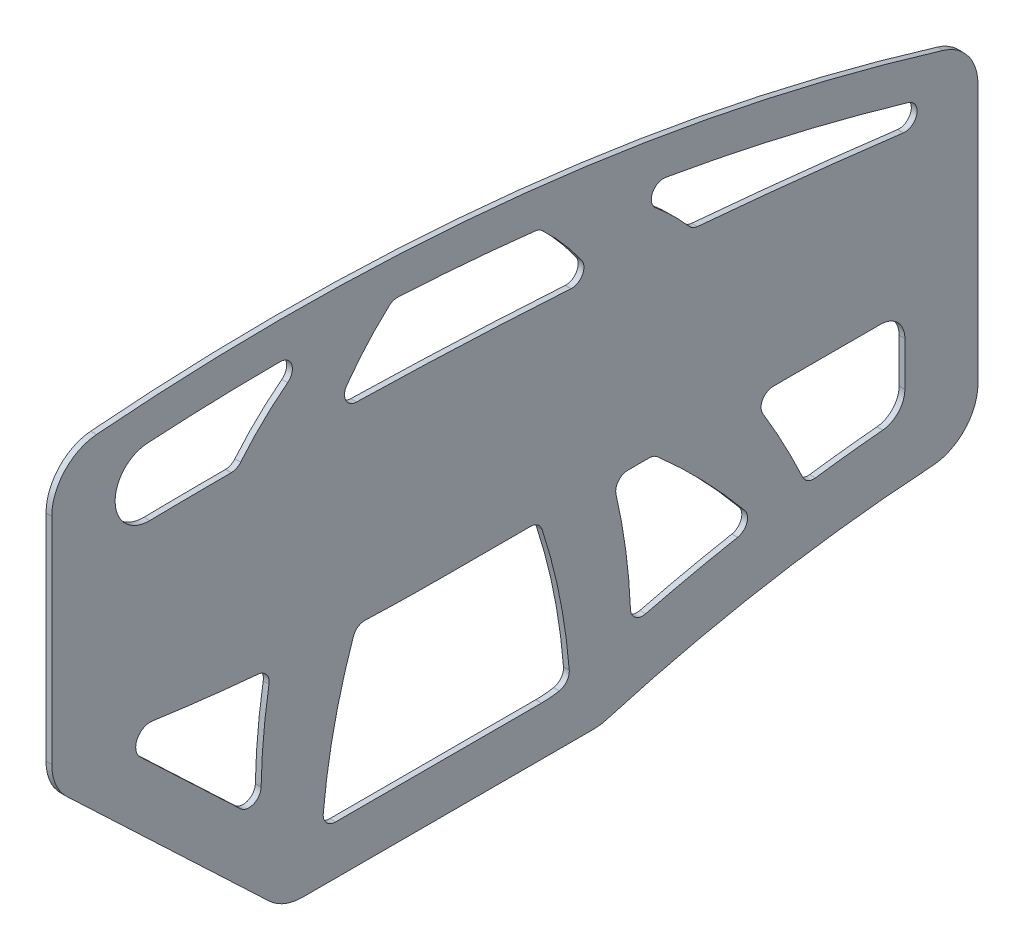
SolidWorks part; units mm, degrees
ref_plane "Front Plane" through (0, 0, 0) normal (0, 0, 1) x (1, 0, 0)
ref_plane "Top Plane" through (0, 0, 0) normal (0, 1, 0) x (1, 0, 0)
ref_plane "Right Plane" through (0, 0, 0) normal (1, 0, 0) x (0, 0, -1)
sketch "Sketch3" plane through (0, 0, 0) normal (1, 0, 0) x (0, 0, -1)
  line L0 (296.2756, -106.7625) -> (296.2756, 28.1835) construction
  line L1 (-55.5532, -162.7221) -> (95.7836, -162.7221) construction
  line L2 (-178.3931, -55.9359) -> (-73.0219, -155.7613) construction
  line L3 (-186.3244, 74.4801) -> (-186.3244, -37.4967) construction
  line L4 (296.2756, -106.7625) -> (296.2756, 28.1835)
  line L5 (-55.5532, -162.7221) -> (95.7836, -162.7221)
  line L6 (-178.3931, -55.9359) -> (-73.0219, -155.7613)
  line L7 (-186.3244, 74.4801) -> (-186.3244, -37.4967)
  line L8 (-140.2016, -57.1289) -> (-87.9677, -106.6136) construction
  line L9 (-140.2016, -57.1289) -> (-87.9677, -106.6136)
  line L10 (63.1095, -54.7721) -> (16.8756, -54.7721) construction
  line L11 (-38.5414, -137.3221) -> (68.868, -137.3221) construction
  line L12 (63.1095, -54.7721) -> (16.8756, -54.7721)
  line L13 (-38.5414, -137.3221) -> (68.868, -137.3221)
  line L14 (124.985, -54.7721) -> (113.8651, -54.7721) construction
  line L15 (124.985, -54.7721) -> (113.8651, -54.7721)
  line L16 (258.1756, -90.4176) -> (258.1756, -67.4721) construction
  line L17 (245.4756, -54.7721) -> (189.6005, -54.7721) construction
  line L18 (245.4756, -54.7721) -> (189.6005, -54.7721)
  line L19 (258.1756, -90.4176) -> (258.1756, -67.4721)
  arc A0 (296.2756, 28.1835) -> (278.2931, 52.4763) centre (270.8756, 28.1835) ccw construction
  arc A1 (272.4753, -132.1121) -> (296.2756, -106.7625) centre (270.8756, -106.7625) ccw construction
  arc A2 (95.7836, -162.7221) -> (102.8656, -161.7148) centre (95.7836, -137.3221) ccw construction
  arc A3 (272.4753, -132.1121) -> (102.8656, -161.7148) centre (321.9663, -916.3645) ccw construction
  arc A4 (-73.0219, -155.7613) -> (-55.5532, -162.7221) centre (-55.5532, -137.3221) ccw construction
  arc A5 (-186.3244, -37.4967) -> (-178.3931, -55.9359) centre (-160.9244, -37.4967) ccw construction
  arc A6 (-163.0233, 99.7932) -> (-186.3244, 74.4801) centre (-160.9244, 74.4801) ccw construction
  arc A7 (278.2931, 52.4763) -> (-163.0233, 99.7932) centre (-65.6891, -1074.0863) ccw construction
  arc A8 (296.2756, 28.1835) -> (278.2931, 52.4763) centre (270.8756, 28.1835) ccw
  arc A9 (272.4753, -132.1121) -> (296.2756, -106.7625) centre (270.8756, -106.7625) ccw
  arc A10 (95.7836, -162.7221) -> (102.8656, -161.7148) centre (95.7836, -137.3221) ccw
  arc A11 (272.4753, -132.1121) -> (102.8656, -161.7148) centre (321.9663, -916.3645) ccw
  arc A12 (-73.0219, -155.7613) -> (-55.5532, -162.7221) centre (-55.5532, -137.3221) ccw
  arc A13 (-186.3244, -37.4967) -> (-178.3931, -55.9359) centre (-160.9244, -37.4967) ccw
  arc A14 (-163.0233, 99.7932) -> (-186.3244, 74.4801) centre (-160.9244, 74.4801) ccw
  arc A15 (278.2931, 52.4763) -> (-163.0233, 99.7932) centre (-65.6891, -1074.0863) ccw
  arc A16 (-63.4237, 73.3867) -> (-67.3033, 84.7705) centre (-67.2945, 78.4205) ccw construction
  arc A17 (-67.3033, 84.7705) -> (-136.6126, 82.5993) centre (-65.6891, -1074.0863) ccw construction
  arc A18 (-136.6126, 82.5993) -> (-135.2401, 47.0749) centre (-135.5244, 64.8526) ccw construction
  arc A19 (-92.8258, 47.4311) -> (-135.2401, 47.0749) centre (-90.5684, -2746.568) ccw construction
  arc A20 (-92.8258, 47.4311) -> (-87.9387, 49.7329) centre (-92.831, 53.7811) ccw construction
  arc A21 (-63.4237, 73.3867) -> (-87.9387, 49.7329) centre (29.4753, -47.4253) ccw construction
  arc A22 (-63.4237, 73.3867) -> (-67.3033, 84.7705) centre (-67.2945, 78.4205) ccw
  arc A23 (-67.3033, 84.7705) -> (-136.6126, 82.5993) centre (-65.6891, -1074.0863) ccw
  arc A24 (-136.6126, 82.5993) -> (-135.2401, 47.0749) centre (-135.5244, 64.8526) ccw
  arc A25 (-92.8258, 47.4311) -> (-135.2401, 47.0749) centre (-90.5684, -2746.568) ccw
  arc A26 (-92.8258, 47.4311) -> (-87.9387, 49.7329) centre (-92.831, 53.7811) ccw
  arc A27 (-63.4237, 73.3867) -> (-87.9387, 49.7329) centre (29.4753, -47.4253) ccw
  arc A28 (69.2315, 75.6347) -> (65.6099, 77.3095) centre (64.8904, 71.0004) ccw construction
  arc A29 (89.7981, 51.9454) -> (69.2315, 75.6347) centre (-34.9549, -35.5901) ccw construction
  arc A30 (84.2029, 41.9605) -> (89.7981, 51.9454) centre (84.6001, 48.2981) ccw construction
  arc A31 (84.2029, 41.9605) -> (-27.5702, 46.7217) centre (-90.5684, -2746.568) ccw construction
  arc A32 (-32.6046, 56.7463) -> (-27.5702, 46.7217) centre (-27.427, 53.0701) ccw construction
  arc A33 (-10.5082, 81.5997) -> (-32.6046, 56.7463) centre (91.6585, -31.4832) ccw construction
  arc A34 (-5.9237, 83.2295) -> (-10.5082, 81.5997) centre (-6.2512, 76.8879) ccw construction
  arc A35 (65.6099, 77.3095) -> (-5.9237, 83.2295) centre (-65.6891, -1074.0863) ccw construction
  arc A36 (69.2315, 75.6347) -> (65.6099, 77.3095) centre (64.8904, 71.0004) ccw
  arc A37 (89.7981, 51.9454) -> (69.2315, 75.6347) centre (-34.9549, -35.5901) ccw
  arc A38 (84.2029, 41.9605) -> (89.7981, 51.9454) centre (84.6001, 48.2981) ccw
  arc A39 (84.2029, 41.9605) -> (-27.5702, 46.7217) centre (-90.5684, -2746.568) ccw
  arc A40 (-32.6046, 56.7463) -> (-27.5702, 46.7217) centre (-27.427, 53.0701) ccw
  arc A41 (-10.5082, 81.5997) -> (-32.6046, 56.7463) centre (91.6585, -31.4832) ccw
  arc A42 (-5.9237, 83.2295) -> (-10.5082, 81.5997) centre (-6.2512, 76.8879) ccw
  arc A43 (65.6099, 77.3095) -> (-5.9237, 83.2295) centre (-65.6891, -1074.0863) ccw
  arc A44 (145.8584, 39.2137) -> (150.1096, 37.0466) centre (150.6566, 43.373) ccw construction
  arc A45 (257.3848, 25.681) -> (150.1096, 37.0466) centre (-90.5684, -2746.568) ccw construction
  arc A46 (145.8584, 39.2137) -> (128.3574, 56.391) centre (30.7017, -60.6096) ccw construction
  arc A47 (133.5179, 67.5215) -> (128.3574, 56.391) centre (132.4264, 61.266) ccw construction
  arc A48 (259.96, 38.0757) -> (133.5179, 67.5215) centre (-65.6891, -1074.0863) ccw construction
  arc A49 (257.3848, 25.681) -> (259.96, 38.0757) centre (258.1756, 31.9816) ccw construction
  arc A50 (145.8584, 39.2137) -> (150.1096, 37.0466) centre (150.6566, 43.373) ccw
  arc A51 (257.3848, 25.681) -> (150.1096, 37.0466) centre (-90.5684, -2746.568) ccw
  arc A52 (145.8584, 39.2137) -> (128.3574, 56.391) centre (30.7017, -60.6096) ccw
  arc A53 (133.5179, 67.5215) -> (128.3574, 56.391) centre (132.4264, 61.266) ccw
  arc A54 (259.96, 38.0757) -> (133.5179, 67.5215) centre (-65.6891, -1074.0863) ccw
  arc A55 (257.3848, 25.681) -> (259.96, 38.0757) centre (258.1756, 31.9816) ccw
  arc A56 (-133.883, -44.0537) -> (-140.2016, -57.1289) centre (-134.961, -51.5971) ccw construction
  arc A57 (-73.1466, -57.8349) -> (-78.8395, -50.4647) centre (-79.4099, -56.789) ccw construction
  arc A58 (-133.883, -44.0537) -> (-78.8395, -50.4647) centre (16.8756, 1010.831) ccw construction
  arc A59 (-87.9677, -106.6136) -> (-77.2517, -102.1269) centre (-83.6005, -102.0038) ccw construction
  arc A60 (-73.1466, -57.8349) -> (-77.2517, -102.1269) centre (227.491, -108.0353) ccw construction
  arc A61 (-133.883, -44.0537) -> (-140.2016, -57.1289) centre (-134.961, -51.5971) ccw
  arc A62 (-73.1466, -57.8349) -> (-78.8395, -50.4647) centre (-79.4099, -56.789) ccw
  arc A63 (-133.883, -44.0537) -> (-78.8395, -50.4647) centre (16.8756, 1010.831) ccw
  arc A64 (-87.9677, -106.6136) -> (-77.2517, -102.1269) centre (-83.6005, -102.0038) ccw
  arc A65 (-73.1466, -57.8349) -> (-77.2517, -102.1269) centre (227.491, -108.0353) ccw
  arc A66 (69.1444, -59.1464) -> (63.1095, -54.7721) centre (63.1095, -61.1221) ccw construction
  arc A67 (-22.9289, -54.0284) -> (16.8756, -54.7721) centre (16.8756, 1010.831) ccw construction
  arc A68 (-22.9289, -54.0284) -> (-29.1615, -58.2816) centre (-23.1661, -60.374) ccw construction
  arc A69 (-29.1615, -58.2816) -> (-44.8639, -130.3818) centre (258.6163, -158.7156) ccw construction
  arc A70 (-44.8639, -130.3818) -> (-38.5414, -137.3221) centre (-38.5414, -130.9721) ccw construction
  arc A71 (68.868, -137.3221) -> (78.1338, -136.4699) centre (68.868, -86.5221) ccw construction
  arc A72 (78.1338, -136.4699) -> (83.3054, -129.7211) centre (76.9756, -130.2264) ccw construction
  arc A73 (83.3054, -129.7211) -> (69.1444, -59.1464) centre (-220.5278, -153.9783) ccw construction
  arc A74 (69.1444, -59.1464) -> (63.1095, -54.7721) centre (63.1095, -61.1221) ccw
  arc A75 (-22.9289, -54.0284) -> (16.8756, -54.7721) centre (16.8756, 1010.831) ccw
  arc A76 (-22.9289, -54.0284) -> (-29.1615, -58.2816) centre (-23.1661, -60.374) ccw
  arc A77 (-29.1615, -58.2816) -> (-44.8639, -130.3818) centre (258.6163, -158.7156) ccw
  arc A78 (-44.8639, -130.3818) -> (-38.5414, -137.3221) centre (-38.5414, -130.9721) ccw
  arc A79 (68.868, -137.3221) -> (78.1338, -136.4699) centre (68.868, -86.5221) ccw
  arc A80 (78.1338, -136.4699) -> (83.3054, -129.7211) centre (76.9756, -130.2264) ccw
  arc A81 (83.3054, -129.7211) -> (69.1444, -59.1464) centre (-220.5278, -153.9783) ccw
  arc A82 (171.027, -113.651) -> (174.7543, -103.3725) centre (169.8535, -107.4104) ccw construction
  arc A83 (171.027, -113.651) -> (123.0997, -124.1627) centre (321.9663, -916.3645) ccw construction
  arc A84 (115.2092, -118.2703) -> (123.0997, -124.1627) centre (121.5536, -118.0038) ccw construction
  arc A85 (115.2092, -118.2703) -> (107.6776, -62.5495) centre (-189.3222, -131.0632) ccw construction
  arc A86 (113.8651, -54.7721) -> (107.6776, -62.5495) centre (113.8651, -61.1221) ccw construction
  arc A87 (129.1736, -56.3494) -> (124.985, -54.7721) centre (124.985, -61.1221) ccw construction
  arc A88 (174.7543, -103.3725) -> (129.1736, -56.3494) centre (-138.896, -361.7993) ccw construction
  arc A89 (171.027, -113.651) -> (174.7543, -103.3725) centre (169.8535, -107.4104) ccw
  arc A90 (171.027, -113.651) -> (123.0997, -124.1627) centre (321.9663, -916.3645) ccw
  arc A91 (115.2092, -118.2703) -> (123.0997, -124.1627) centre (121.5536, -118.0038) ccw
  arc A92 (115.2092, -118.2703) -> (107.6776, -62.5495) centre (-189.3222, -131.0632) ccw
  arc A93 (113.8651, -54.7721) -> (107.6776, -62.5495) centre (113.8651, -61.1221) ccw
  arc A94 (129.1736, -56.3494) -> (124.985, -54.7721) centre (124.985, -61.1221) ccw
  arc A95 (174.7543, -103.3725) -> (129.1736, -56.3494) centre (-138.896, -361.7993) ccw
  arc A96 (258.1756, -67.4721) -> (245.4756, -54.7721) centre (245.4756, -67.4721) ccw construction
  arc A97 (246.6467, -103.0635) -> (258.1756, -90.4176) centre (245.4756, -90.4176) ccw construction
  arc A98 (246.6467, -103.0635) -> (211.5465, -107.0815) centre (321.9663, -916.3645) ccw construction
  arc A99 (204.9272, -103.4609) -> (211.5465, -107.0815) centre (210.6881, -100.7898) ccw construction
  arc A100 (204.9272, -103.4609) -> (184.1641, -64.4035) centre (-163.7678, -274.4138) ccw construction
  arc A101 (189.6005, -54.7721) -> (184.1641, -64.4035) centre (189.6005, -61.1221) ccw construction
  arc A102 (246.6467, -103.0635) -> (258.1756, -90.4176) centre (245.4756, -90.4176) ccw
  arc A103 (246.6467, -103.0635) -> (211.5465, -107.0815) centre (321.9663, -916.3645) ccw
  arc A104 (204.9272, -103.4609) -> (211.5465, -107.0815) centre (210.6881, -100.7898) ccw
  arc A105 (204.9272, -103.4609) -> (184.1641, -64.4035) centre (-163.7678, -274.4138) ccw
  arc A106 (189.6005, -54.7721) -> (184.1641, -64.4035) centre (189.6005, -61.1221) ccw
  arc A107 (258.1756, -67.4721) -> (245.4756, -54.7721) centre (245.4756, -67.4721) ccw
extrude "Boss-Extrude1" add sketch "Sketch3" along normal blind 3 separate body
